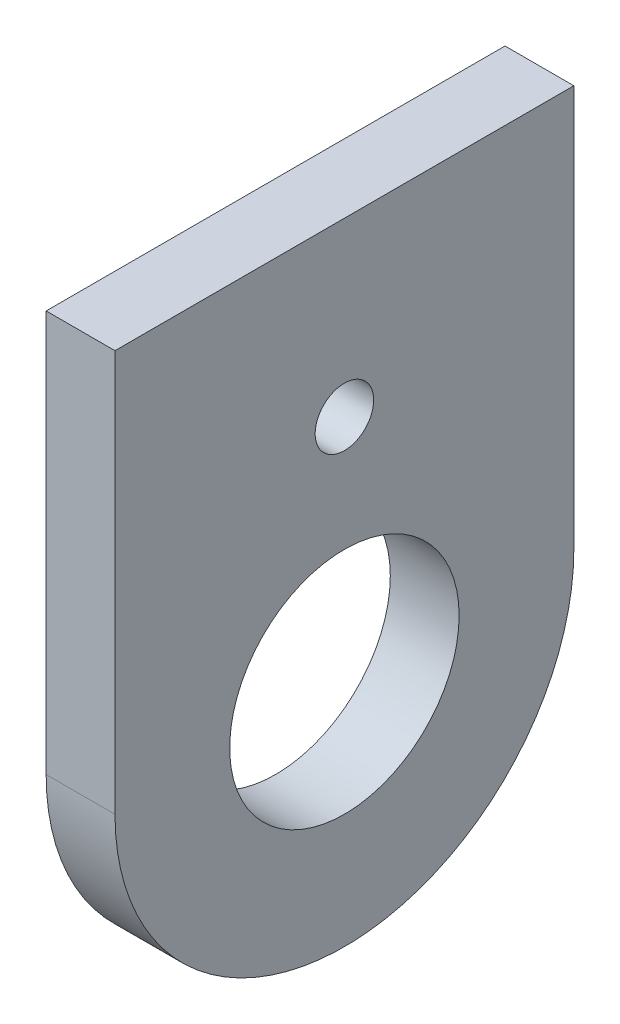
SolidWorks part; units mm, degrees
material "Q355"
ref_plane "前视基准面" through (0, 0, 0) normal (0, 0, 1) x (1, 0, 0)
ref_plane "上视基准面" through (0, 0, 0) normal (0, 1, 0) x (1, 0, 0)
ref_plane "右视基准面" through (0, 0, 0) normal (1, 0, 0) x (0, 0, -1)
sketch "草图1" plane through (0, 0, 0) normal (1, 0, 0) x (0, 0, -1)
  line L0 (0, 0) -> (0, 93.0871) construction
  line L1 (-40, 0) -> (-40, 70)
  line L2 (-40, 70) -> (40, 70)
  line L3 (40, 70) -> (40, 0)
  circle A0 centre (0, 0) radius 20
  arc A1 (-40, 0) -> (40, 0) centre (0, 0) ccw
  dimension "D1" = 70
  dimension "D3" = 40
  dimension "D2" = 80
extrude "凸台-拉伸1" add sketch "草图1" along normal blind 12
hole_wizard "M12 螺纹孔1" positions "草图2" profile "草图3" tap size "M12" standard "GB" end condition through all
sketch "草图2" plane through (12, 0, 0) normal (1, 0, 0) x (0, 0, -1)
  point P0 (0, 40)
  dimension "D1" = 40
sketch "草图3" plane through (12, 40, 0) normal (0, 1, 0) x (0, 0, -1)
  line L0 (0, 0) -> (0, 12)
  line L1 (0, 12) -> (5.1, 12)
  line L2 (5.1, 12) -> (5.1, 0)
  line L5 (5.1, 0) -> (0, 0)
  line L11 (0, -6.35) -> (0, 107.95) construction
  dimension "通孔螺纹孔钻头直径" = 10.2
  dimension "通孔螺纹孔钻头深度" = 12
cosmetic thread "孔螺蚊线1" parameters "D2"=12
